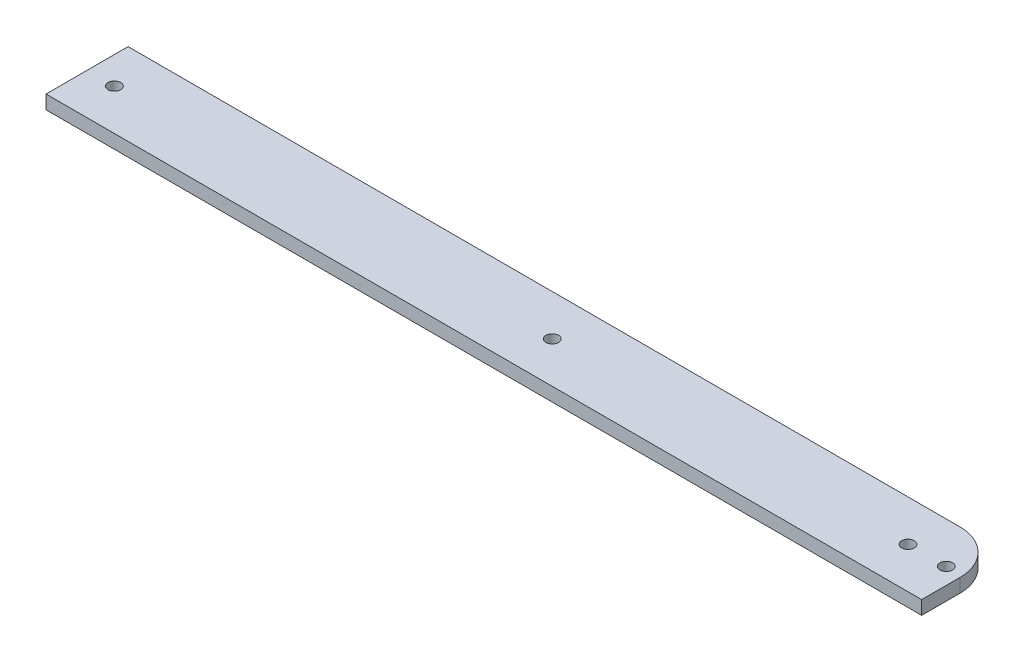
SolidWorks part; units mm, degrees
ref_plane "Front Plane" through (0, 0, 0) normal (0, 0, 1) x (1, 0, 0)
ref_plane "Top Plane" through (0, 0, 0) normal (0, 1, 0) x (1, 0, 0)
ref_plane "Right Plane" through (0, 0, 0) normal (1, 0, 0) x (0, 0, -1)
sketch "Sketch1" plane through (0, 0, 0) normal (0, 1, 0) x (1, 0, 0)
  line L1 (0, 0) -> (203.2, 0)
  line L2 (0, 0) -> (0, 19.05)
  line L3 (0, 19.05) -> (203.2, 19.05)
  line L4 (203.2, 0) -> (203.2, 19.05)
  circle A0 centre (6.35, 9.525) radius 1.4605
  circle A1 centre (107.95, 9.525) radius 1.4605
  dimension "D3" = 2.921
  dimension "D6" = 2.921
  dimension "D8" = 107.95
  dimension "D1" = 203.2
  dimension "D2" = 19.05
  dimension "D4" = 6.35
  dimension "D5" = 9.525
  dimension "D7" = 9.525
extrude "Boss-Extrude1" add sketch "Sketch1" along normal blind 3.175
sketch "Sketch2" plane through (0, 0, 0) normal (0, -1, 0) x (-1, 0, 0)
  line L0 (-203.2, 0) -> (-203.2, 19.05) construction
  line L1 (0, 0) -> (-203.2, 0) construction
  circle A0 centre (-199.39, 9.525) radius 1.4605
  circle A1 centre (-190.5, 9.525) radius 1.4605
  point P10 (-199.5863, 125.506)
  dimension "D1" = 2.921
  dimension "D4" = 2.921
  dimension "D2" = 3.81
  dimension "D3" = 9.525
  dimension "D5" = 12.7
  dimension "D6" = 9.525
extrude "Cut-Extrude1" cut sketch "Sketch2" against normal through all
fillet "Fillet1" radius 10.16 1 edges at (203.2, 1.5875, -19.05)
equation "\"0.305n\"=0.3"
